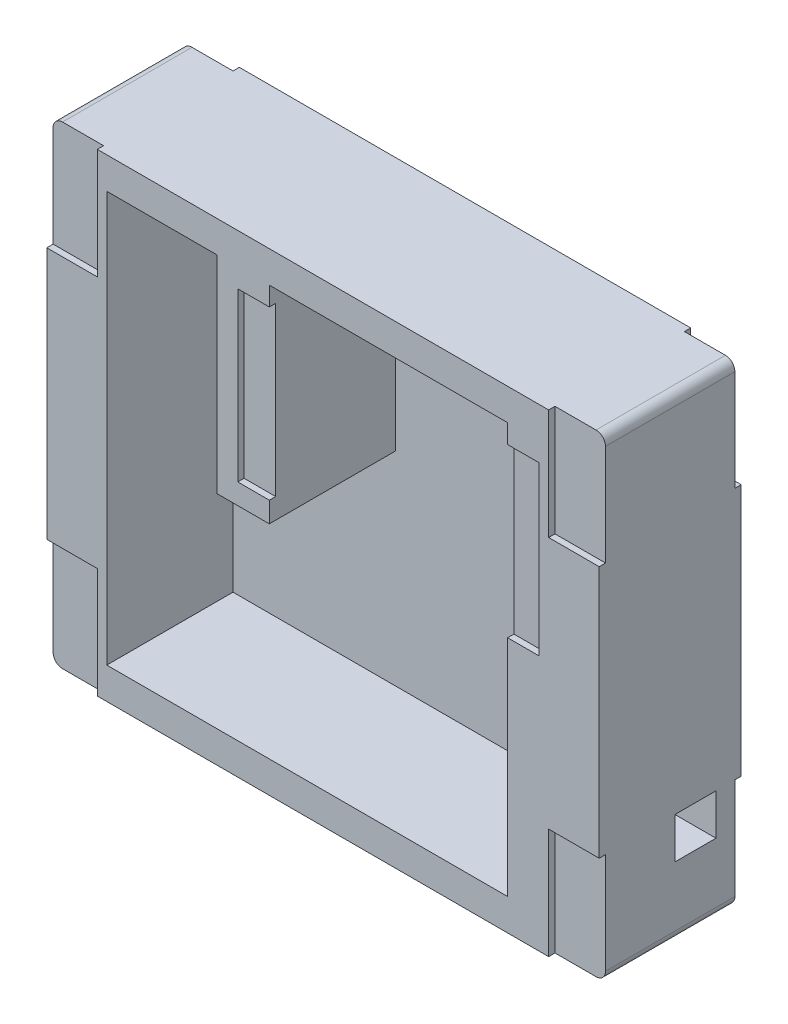
SolidWorks part; units mm, degrees
ref_plane "Front Plane" through (0, 0, 0) normal (0, 0, 1) x (1, 0, 0)
ref_plane "Top Plane" through (0, 0, 0) normal (0, 1, 0) x (1, 0, 0)
ref_plane "Right Plane" through (0, 0, 0) normal (1, 0, 0) x (0, 0, -1)
sketch "Sketch2" plane through (0, 0, 0) normal (0, 0, 1) x (1, 0, 0)
  line L1 (0, 0) -> (-175, 0)
  line L2 (0, 0) -> (0, -150)
  line L3 (0, -150) -> (-175, -150)
  line L4 (-175, 0) -> (-175, -150)
  dimension "D1" = 175
  dimension "D2" = 150
extrude "Boss-Extrude1" add sketch "Sketch2" along normal blind 45
sketch "Sketch3" plane through (0, 0, 45) normal (0, 0, 1) x (1, 0, 0)
  line L0 (0, 0) -> (-175, 0) construction
  line L1 (-104.5, -10) -> (-29, -10)
  line L2 (-104.5, -10) -> (-104.5, -100)
  line L4 (-29, -10) -> (-29, -140)
  line L5 (-156, -140) -> (-29, -140)
  line L6 (-175, -150) -> (0, -150) construction
  line L8 (-175, 0) -> (-175, -150) construction
  line L9 (0, -150) -> (0, 0) construction
  line L10 (-156, -100) -> (-104.5, -100)
  line L11 (-156, -100) -> (-156, -140)
  dimension "D1" = 10
  dimension "D2" = 75.5
  dimension "D3" = 10
  dimension "D4" = 29
  dimension "D5" = 19
  dimension "D7" = 100
extrude "Cut-Extrude1" cut sketch "Sketch3" against normal blind 40
sketch "Sketch5" plane through (0, 0, 0) normal (1, 0, 0) x (0, 0, -1)
  line L0 (-45, -150) -> (0, -150) construction
  line L1 (-21, -115) -> (-8, -115)
  line L2 (-21, -115) -> (-21, -128)
  line L3 (-21, -128) -> (-8, -128)
  line L4 (-8, -115) -> (-8, -128)
  line L6 (-45, -150) -> (-45, 0) construction
  point P4 (-14.5, -128)
  dimension "D1" = 22
  dimension "D2" = 13
  dimension "D3" = 13
  dimension "D4" = 24
extrude "Cut-Extrude3" cut sketch "Sketch5" against normal blind 50
sketch "Sketch6" plane through (0, 0, 45) normal (0, 0, 1) x (1, 0, 0)
  line L0 (-104.5, -10) -> (-104.5, -100) construction
  line L1 (-114.5, -16) -> (-104.5, -16)
  line L2 (-114.5, -16) -> (-114.5, -69)
  line L3 (-114.5, -69) -> (-104.5, -69)
  line L4 (-104.5, -16) -> (-104.5, -69)
  line L5 (-29, -140) -> (-29, -10) construction
  line L6 (-29, -16) -> (-19, -16)
  line L7 (-29, -16) -> (-29, -69)
  line L8 (-29, -69) -> (-19, -69)
  line L9 (-19, -16) -> (-19, -69)
  line L10 (0, 0) -> (-175, 0) construction
  point P12 (-109.5, -16)
  dimension "D1" = 53
  dimension "D2" = 53
  dimension "D3" = 16
  dimension "D4" = 16
  dimension "D5" = 10
  dimension "D6" = 10
extrude "Cut-Extrude4" cut sketch "Sketch6" against normal blind 2
sketch "Sketch7" plane through (0, 0, 45) normal (0, 0, 1) x (1, 0, 0)
  line L0 (0, 0) -> (-175, 0) construction
  line L1 (-156, -10) -> (-121, -10)
  line L2 (-156, -10) -> (-156, -140)
  line L3 (-156, -140) -> (-121, -140)
  line L4 (-121, -10) -> (-121, -140)
  line L5 (-175, 0) -> (-175, -150) construction
  line L7 (-175, -150) -> (0, -150) construction
  dimension "D1" = 10
  dimension "D2" = 35
  dimension "D3" = 19
  dimension "D4" = 10
extrude "Cut-Extrude5" cut sketch "Sketch7" against normal blind 40
sketch "Sketch9" plane through (0, 0, 45) normal (0, 0, 1) x (1, 0, 0)
  line L1 (-175, 0) -> (-159, 0)
  line L2 (-175, 0) -> (-175, -35)
  line L3 (-175, -35) -> (-159, -35)
  line L4 (-159, 0) -> (-159, -35)
  line L5 (-175, -150) -> (-159, -150)
  line L6 (-175, -150) -> (-175, -115)
  line L7 (-175, -115) -> (-159, -115)
  line L8 (-159, -150) -> (-159, -115)
  line L9 (0, -150) -> (-16, -150)
  line L10 (0, -150) -> (0, -115)
  line L11 (0, -115) -> (-16, -115)
  line L12 (-16, -150) -> (-16, -115)
  line L13 (0, 0) -> (-16, 0)
  line L14 (0, 0) -> (0, -35)
  line L15 (0, -35) -> (-16, -35)
  line L16 (-16, 0) -> (-16, -35)
  dimension "D1" = 16
  dimension "D2" = 35
extrude "Cut-Extrude6" cut sketch "Sketch9" against normal blind 2
sketch "Sketch10" plane through (0, 0, 45) normal (0, 0, 1) x (1, 0, 0)
  line L0 (-104.5, -69) -> (-104.5, -100) construction
  line L1 (-121, -100) -> (-104.5, -100)
  line L2 (-121, -100) -> (-121, -75.5)
  line L3 (-121, -75.5) -> (-104.5, -75.5)
  line L4 (-104.5, -100) -> (-104.5, -75.5)
  dimension "D1" = 24.5
extrude "Cut-Extrude7" cut sketch "Sketch10" against normal blind 40
sketch "Sketch11" plane through (0, 0, 0) normal (0, 0, -1) x (-1, 0, 0)
  line L1 (0, 0) -> (16, 0)
  line L2 (0, 0) -> (0, -35)
  line L3 (0, -35) -> (16, -35)
  line L4 (16, 0) -> (16, -35)
  line L5 (0, -150) -> (16, -150)
  line L6 (0, -150) -> (0, -115)
  line L7 (0, -115) -> (16, -115)
  line L8 (16, -150) -> (16, -115)
  line L9 (175, -150) -> (159, -150)
  line L10 (175, -150) -> (175, -115)
  line L11 (175, -115) -> (159, -115)
  line L12 (159, -150) -> (159, -115)
  line L13 (175, 0) -> (159, 0)
  line L14 (175, 0) -> (175, -35)
  line L15 (175, -35) -> (159, -35)
  line L16 (159, 0) -> (159, -35)
  point P20 (8, -35)
  dimension "D1" = 35
  dimension "D2" = 16
extrude "Cut-Extrude8" cut sketch "Sketch11" against normal blind 2
fillet "Fillet1" radius 3 4 edges at (-175, -150, 22.5) (0, -150, 22.5) (0, 0, 22.5) (-175, 0, 22.5)
